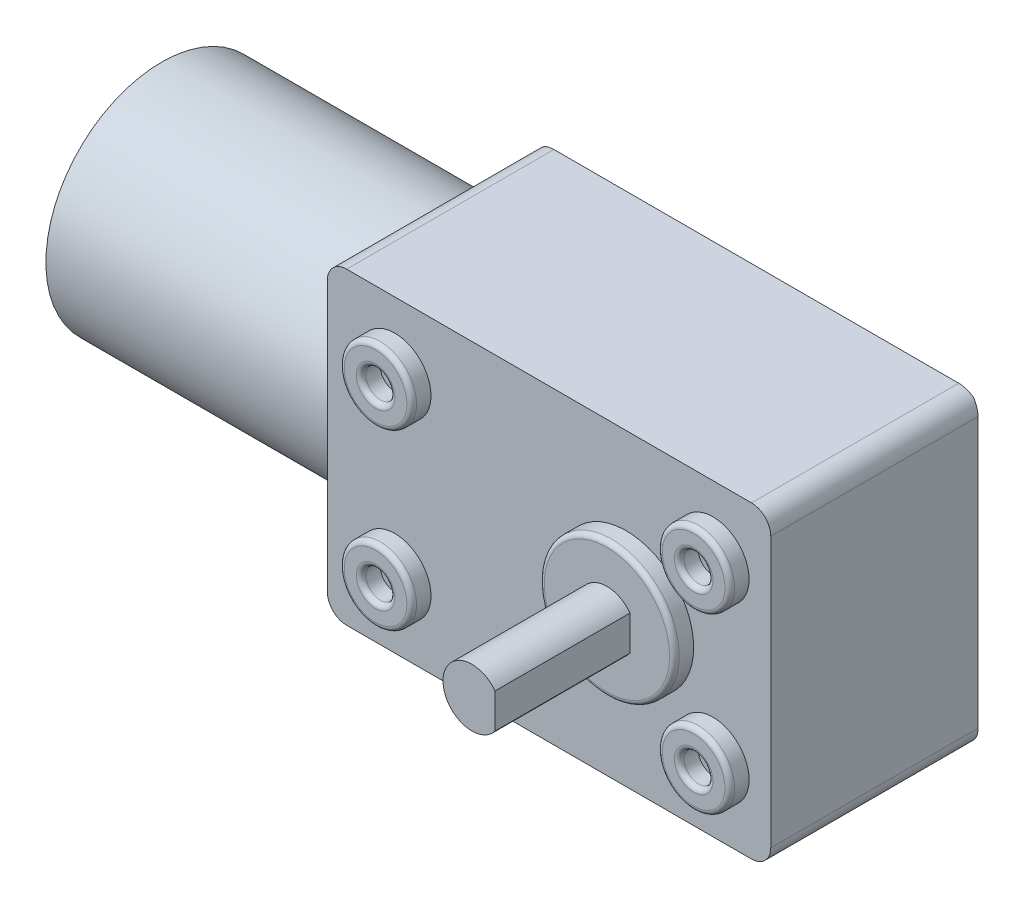
SolidWorks part; units mm, degrees
ref_plane "Front Plane" through (0, 0, 0) normal (0, 0, 1) x (1, 0, 0)
ref_plane "Top Plane" through (0, 0, 0) normal (0, 1, 0) x (1, 0, 0)
ref_plane "Right Plane" through (0, 0, 0) normal (1, 0, 0) x (0, 0, -1)
sketch "Sketch3" plane through (0, 0, 0) normal (0, 0, 1) x (1, 0, 0)
  line L1 (-23, 16) -> (23, 16)
  line L2 (-23, 16) -> (-23, -16)
  line L3 (-23, -16) -> (23, -16)
  line L4 (23, 16) -> (23, -16)
  line L5 (-23, 16) -> (23, -16) construction
  line L6 (-23, -16) -> (23, 16) construction
  point P0 (0, 0)
  dimension "D1" = 46
  dimension "D2" = 32
extrude "Boss-Extrude1" add sketch "Sketch3" along normal blind 22.4
sketch "Sketch4" plane through (0, 0, 22.4) normal (0, 0, 1) x (1, 0, 0)
  line L0 (-23, 16) -> (-23, -16) construction
  line L1 (23, -16) -> (23, 16) construction
  line L2 (-23, -16) -> (23, -16) construction
  line L3 (23, 16) -> (-23, 16) construction
  circle A0 centre (-16, 9) radius 3.75
  circle A1 centre (-16, -9) radius 3.75
  circle A2 centre (17, 9) radius 3.75
  circle A3 centre (17, -9) radius 3.75
  circle A4 centre (17, -9) radius 1.5
  circle A5 centre (-16, -9) radius 1.5
  circle A6 centre (-16, 9) radius 1.5
  circle A7 centre (17, 9) radius 1.5
  circle A8 centre (8, 0) radius 7
  dimension "D1" = 7.5
  dimension "D10" = 3
  dimension "D11" = 14
  dimension "D2" = 7
  dimension "D3" = 7
  dimension "D4" = 6
  dimension "D5" = 6
  dimension "D6" = 7
  dimension "D7" = 7
  dimension "D8" = 7
  dimension "D9" = 7
  dimension "D12" = 15
extrude "Boss-Extrude3" add sketch "Sketch4" along normal blind 2
fillet "Fillet2" radius 0.5 9 edges at (-14.5, -9, 24.4) (-12.25, -9, 24.4) (15, 0, 24.4) (18.5, 9, 24.4) (20.75, 9, 24.4) (-14.5, 9, 24.4) (-12.25, 9, 24.4) (20.75, -9, 24.4) (18.5, -9, 24.4)
chamfer "Chamfer2" distance 5 distance2 0.9 3 edges at (0, 16, 0) (23, 0, 0) (0, -16, 0)
fillet "Fillet3" radius 2 4 edges at (23, -16, 11.65) (23, 16, 11.65) (-23, 16, 11.65) (-23, -16, 11.65)
sketch "Sketch8" plane through (-23, 0, 0) normal (-1, 0, 0) x (0, 0, 1)
  line L0 (22.4, 14) -> (22.4, -14) construction
  circle A0 centre (9.4, 0) radius 12
  dimension "D1" = 24
  dimension "D2" = 13
extrude "Boss-Extrude5" add sketch "Sketch8" along normal blind 30.2
sketch "Sketch9" plane through (-53.2, 0, 0) normal (-1, 0, 0) x (0, 0, 1)
  circle A0 centre (9.8172, 0) radius 11.5
  dimension "D1" = 23
extrude "Cut-Extrude1" cut sketch "Sketch9" against normal blind 1
sketch "Sketch10" plane through (0, 0, 24.4) normal (0, 0, 1) x (1, 0, 0)
  line L0 (8, 6.5) -> (8, -6.5) construction
  line L1 (10.4, 1.8) -> (10.4, -1.8)
  line L2 (5, 0) -> (5, -3.3977) construction
  circle A0 centre (8, 0) radius 6.5 construction
  arc A1 (10.4, 1.8) -> (10.4, -1.8) centre (8, 0) ccw
  dimension "D1" = 6
  dimension "D2" = 5.4
extrude "Boss-Extrude6" add sketch "Sketch10" along normal blind 14
